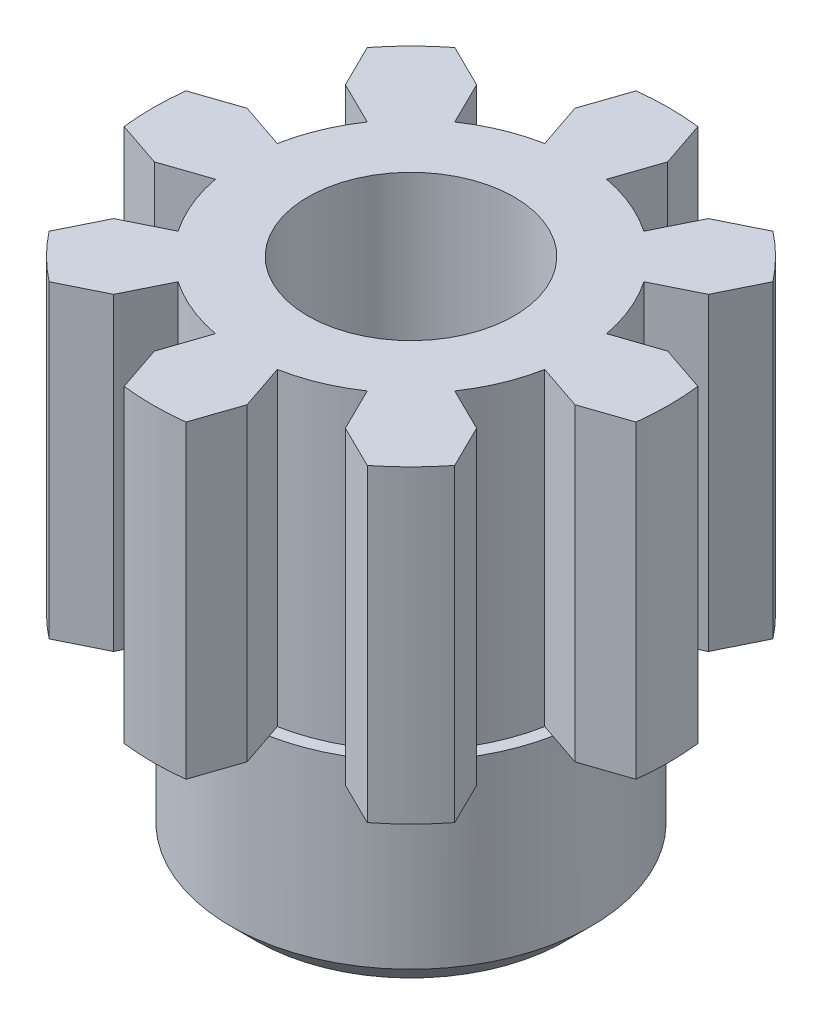
SolidWorks part; units mm, degrees
material "ABS"
ref_plane "Front Plane" through (0, 0, 0) normal (0, 0, 1) x (1, 0, 0)
ref_plane "Top Plane" through (0, 0, 0) normal (0, 1, 0) x (1, 0, 0)
ref_plane "Right Plane" through (0, 0, 0) normal (1, 0, 0) x (0, 0, -1)
sketch "Sketch1" plane through (0, 0, 0) normal (0, 0, 1) x (1, 0, 0)
  line L0 (0, -2) -> (0, 3) construction
  line L1 (1, 3) -> (2.5, 3)
  line L2 (2.5, 3) -> (2.5, 0)
  line L3 (2.5, 0) -> (1.75, 0)
  line L4 (1.75, 0) -> (1.75, -1.75)
  line L5 (1.5, -2) -> (1, -2)
  line L6 (1.5, -2) -> (1.75, -1.75)
  line L7 (1, -2) -> (1, 3)
  dimension "D1" = 5
  dimension "D2" = 3.5
  dimension "D3" = 3
  dimension "D4" = 5
  dimension "D5" = 45
  dimension "D6" = 0.25
  dimension "D7" = 2
revolve "Revolve1" add sketch "Sketch1" angle 360 about L0
sketch "Sketch2" plane through (0, 3, 0) normal (0, 1, 0) x (1, 0, 0)
  line L0 (-0.3, 2.4819) -> (-0.45, 2.0395)
  line L1 (0, 0) -> (0, 2.5) construction
  line L2 (-0.45, 2.0395) -> (-0.3, 1.5971)
  line L3 (0.45, 2.0395) -> (0.3, 1.5971)
  line L4 (0.3, 2.4819) -> (0.45, 2.0395)
  line L5 (1.5429, 1.9671) -> (1.1239, 1.7603)
  line L6 (1.1239, 1.7603) -> (0.9172, 1.3414)
  line L7 (1.7603, 1.1239) -> (1.3414, 0.9172)
  line L8 (1.9671, 1.5429) -> (1.7603, 1.1239)
  line L9 (2.4819, 0.3) -> (2.0395, 0.45)
  line L10 (2.0395, 0.45) -> (1.5971, 0.3)
  line L11 (2.0395, -0.45) -> (1.5971, -0.3)
  line L12 (2.4819, -0.3) -> (2.0395, -0.45)
  line L13 (1.9671, -1.5429) -> (1.7603, -1.1239)
  line L14 (1.7603, -1.1239) -> (1.3414, -0.9172)
  line L15 (1.1239, -1.7603) -> (0.9172, -1.3414)
  line L16 (1.5429, -1.9671) -> (1.1239, -1.7603)
  line L17 (0.3, -2.4819) -> (0.45, -2.0395)
  line L18 (0.45, -2.0395) -> (0.3, -1.5971)
  line L19 (-0.45, -2.0395) -> (-0.3, -1.5971)
  line L20 (-0.3, -2.4819) -> (-0.45, -2.0395)
  line L21 (-1.5429, -1.9671) -> (-1.1239, -1.7603)
  line L22 (-1.1239, -1.7603) -> (-0.9172, -1.3414)
  line L23 (-1.7603, -1.1239) -> (-1.3414, -0.9172)
  line L24 (-1.9671, -1.5429) -> (-1.7603, -1.1239)
  line L25 (-2.4819, -0.3) -> (-2.0395, -0.45)
  line L26 (-2.0395, -0.45) -> (-1.5971, -0.3)
  line L27 (-2.0395, 0.45) -> (-1.5971, 0.3)
  line L28 (-2.4819, 0.3) -> (-2.0395, 0.45)
  line L29 (-1.9671, 1.5429) -> (-1.7603, 1.1239)
  line L30 (-1.7603, 1.1239) -> (-1.3414, 0.9172)
  line L31 (-1.1239, 1.7603) -> (-0.9172, 1.3414)
  line L32 (-1.5429, 1.9671) -> (-1.1239, 1.7603)
  arc A0 (0.3, 1.5971) -> (0.9172, 1.3414) centre (0, 0) cw
  arc A1 (0.3, 2.4819) -> (1.5429, 1.9671) centre (0, 0) cw
  circle A2 centre (0, 0) radius 2.5 construction
  arc A3 (1.9671, 1.5429) -> (2.4819, 0.3) centre (0, 0) cw
  circle A4 centre (0, 0) radius 1.625 construction
  arc A5 (1.3414, 0.9172) -> (1.5971, 0.3) centre (0, 0) cw
  arc A6 (2.4819, -0.3) -> (1.9671, -1.5429) centre (0, 0) cw
  arc A7 (1.5971, -0.3) -> (1.3414, -0.9172) centre (0, 0) cw
  arc A8 (1.5429, -1.9671) -> (0.3, -2.4819) centre (0, 0) cw
  arc A9 (0.9172, -1.3414) -> (0.3, -1.5971) centre (0, 0) cw
  arc A10 (-0.3, -2.4819) -> (-1.5429, -1.9671) centre (0, 0) cw
  arc A11 (-0.3, -1.5971) -> (-0.9172, -1.3414) centre (0, 0) cw
  arc A12 (-1.9671, -1.5429) -> (-2.4819, -0.3) centre (0, 0) cw
  arc A13 (-1.3414, -0.9172) -> (-1.5971, -0.3) centre (0, 0) cw
  arc A14 (-2.4819, 0.3) -> (-1.9671, 1.5429) centre (0, 0) cw
  arc A15 (-1.5971, 0.3) -> (-1.3414, 0.9172) centre (0, 0) cw
  arc A16 (-1.5429, 1.9671) -> (-0.3, 2.4819) centre (0, 0) cw
  arc A17 (-0.9172, 1.3414) -> (-0.3, 1.5971) centre (0, 0) cw
  point P57 (0, 0)
  point P88 (0, 0)
  dimension "D3" = 8
  dimension "D5" = 3.25
  dimension "D1" = 0.9
  dimension "D2" = 0.6
  dimension "D4" = 8
extrude "Cut-Extrude1" cut sketch "Sketch2" against normal up to surface (3 mm away) up to face at (0, 0, -2.5)
